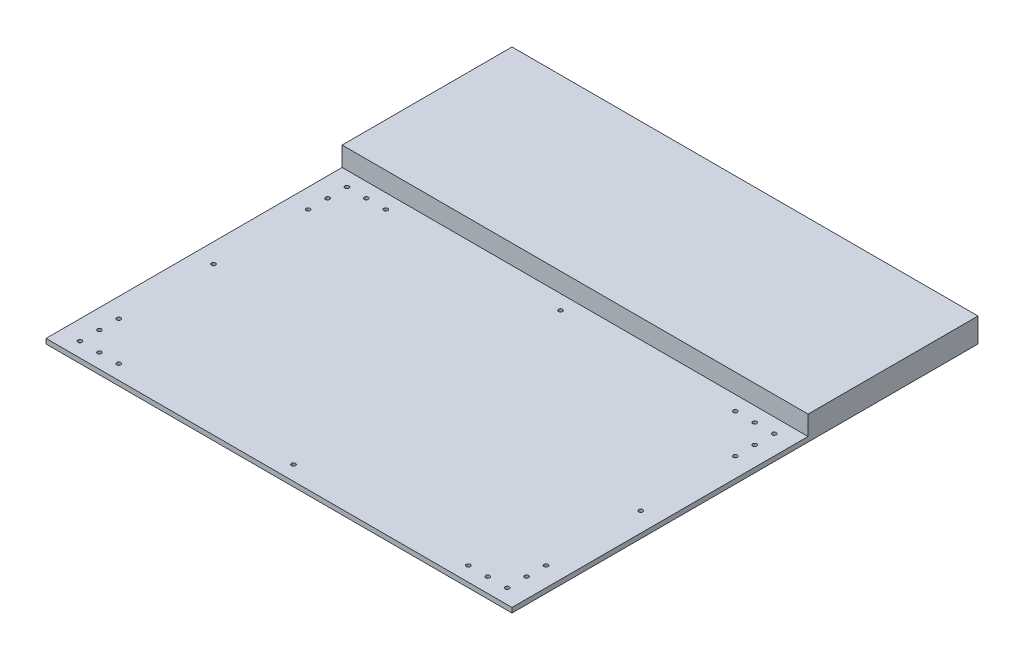
SolidWorks part; units mm, degrees
ref_plane "Front Plane" through (0, 0, 0) normal (0, 0, 1) x (1, 0, 0)
ref_plane "Top Plane" through (0, 0, 0) normal (0, 1, 0) x (1, 0, 0)
ref_plane "Right Plane" through (0, 0, 0) normal (1, 0, 0) x (0, 0, -1)
sketch "Sketch1" plane through (0, 0, 0) normal (0, 1, 0) x (1, 0, 0)
  line L1 (0, 0) -> (609.6, 0)
  line L2 (0, 0) -> (0, 609.6)
  line L3 (0, 609.6) -> (609.6, 609.6)
  line L4 (609.6, 0) -> (609.6, 609.6)
  dimension "D1" = 609.6
  dimension "D2" = 609.6
extrude "Boss-Extrude1" add sketch "Sketch1" along normal blind 6.35
sketch "Sketch2" plane through (0, 6.35, 0) normal (0, 1, 0) x (1, 0, 0)
  line L0 (0, 387.35) -> (609.6, 387.35)
  line L1 (0, 609.6) -> (0, 0) construction
  line L2 (609.6, 0) -> (609.6, 609.6) construction
  line L3 (0, 0) -> (609.6, 0) construction
  line L5 (0, 609.6) -> (609.6, 609.6)
  line L6 (0, 609.6) -> (0, 387.35)
  line L7 (0, 387.35) -> (609.6, 387.35)
  line L8 (0, 609.6) -> (0, 0)
  line L9 (0, 0) -> (609.6, 0)
  line L10 (609.6, 0) -> (609.6, 609.6)
  line L11 (609.6, 609.6) -> (0, 609.6)
  line L12 (0, 387.35) -> (0, 0)
  line L13 (0, 0) -> (609.6, 0)
  line L14 (609.6, 0) -> (609.6, 387.35)
  line L16 (609.6, 609.6) -> (609.6, 387.35)
  dimension "D1" = 387.35
  dimension "D2" = 0
extrude "Boss-Extrude2" add sketch "Sketch2" along normal blind 25.4 contours L6 L5 L16 L7
sketch "Sketch3" plane through (0, 6.35, 0) normal (0, 1, 0) x (1, 0, 0)
  line L0 (25.4, 368.3) -> (25.4, 19.05) construction
  line L2 (0, 0) -> (609.6, 0) construction
  line L3 (0, 387.35) -> (0, 0) construction
  line L4 (584.2, 368.3) -> (584.2, 19.05) construction
  line L5 (609.6, 0) -> (609.6, 387.35) construction
  line L6 (25.4, 19.05) -> (584.2, 19.05) construction
  line L7 (25.4, 368.3) -> (584.2, 368.3) construction
  line L8 (0, 387.35) -> (609.6, 387.35) construction
  line L9 (304.8, 368.3) -> (304.8, 19.05) construction
  line L10 (25.4, 193.675) -> (584.2, 193.675) construction
  point P0 (25.4, 342.9)
  point P1 (25.4, 368.3)
  point P2 (50.8, 368.3)
  point P3 (25.4, 317.5)
  point P8 (76.2, 368.3)
  point P21 (533.4, 368.3)
  point P22 (558.8, 368.3)
  point P23 (584.2, 368.3)
  point P24 (584.2, 342.9)
  point P25 (584.2, 317.5)
  point P26 (584.2, 69.85)
  point P27 (584.2, 44.45)
  point P28 (558.8, 19.05)
  point P29 (533.4, 19.05)
  point P30 (76.2, 19.05)
  point P31 (50.8, 19.05)
  point P32 (25.4, 19.05)
  point P33 (25.4, 44.45)
  point P34 (25.4, 69.85)
  point P36 (304.8, 368.3)
  point P37 (25.4, 193.675)
  point P38 (304.8, 19.05)
  point P39 (584.2, 19.05)
  dimension "D1" = 25.4
  dimension "D2" = 25.4
  dimension "D3" = 19.05
  dimension "D4" = 19.05
  dimension "D5" = 25.4
  dimension "D6" = 25.4
  dimension "D7" = 25.4
  dimension "D8" = 25.4
hole_wizard "Ø5.3 (5.3) Diameter Hole1" positions "Sketch4" profile "Sketch5" hole size "Ø5.3" standard "ANSI Metric" end condition through all
sketch "Sketch4" plane through (0, 6.35, 0) normal (0, 1, 0) x (1, 0, 0)
  line L0 (25.4, 368.3) -> (25.4, 19.05) construction
  point P0 (25.4, 368.3)
  point P3 (50.8, 368.3)
  point P6 (76.2, 368.3)
  point P9 (25.4, 342.9)
  point P12 (25.4, 317.5)
  point P15 (25.4, 69.85)
  point P18 (25.4, 44.45)
  point P21 (25.4, 19.05)
  point P24 (50.8, 19.05)
  point P27 (76.2, 19.05)
  point P30 (304.8, 19.05)
  point P33 (25.4, 193.675)
  point P37 (304.8, 368.3)
  point P40 (584.2, 193.675)
  point P43 (533.4, 368.3)
  point P46 (558.8, 368.3)
  point P49 (584.2, 368.3)
  point P52 (584.2, 342.9)
  point P55 (584.2, 317.5)
  point P58 (584.2, 69.85)
  point P61 (584.2, 44.45)
  point P64 (584.2, 19.05)
  point P67 (558.8, 19.05)
  point P70 (533.4, 19.05)
sketch "Sketch5" plane through (25.4, 6.35, -368.3) normal (1, 0, 0) x (0, 0, 1)
  line L0 (0, 0) -> (0, 6.35)
  line L1 (0, 6.35) -> (2.65, 6.35)
  line L2 (2.65, 6.35) -> (2.65, 0)
  line L5 (2.65, 0) -> (0, 0)
  line L11 (0, -6.35) -> (0, 107.95) construction
  dimension "Thru Hole Dia." = 5.3
  dimension "Thru Hole Depth" = 6.35
